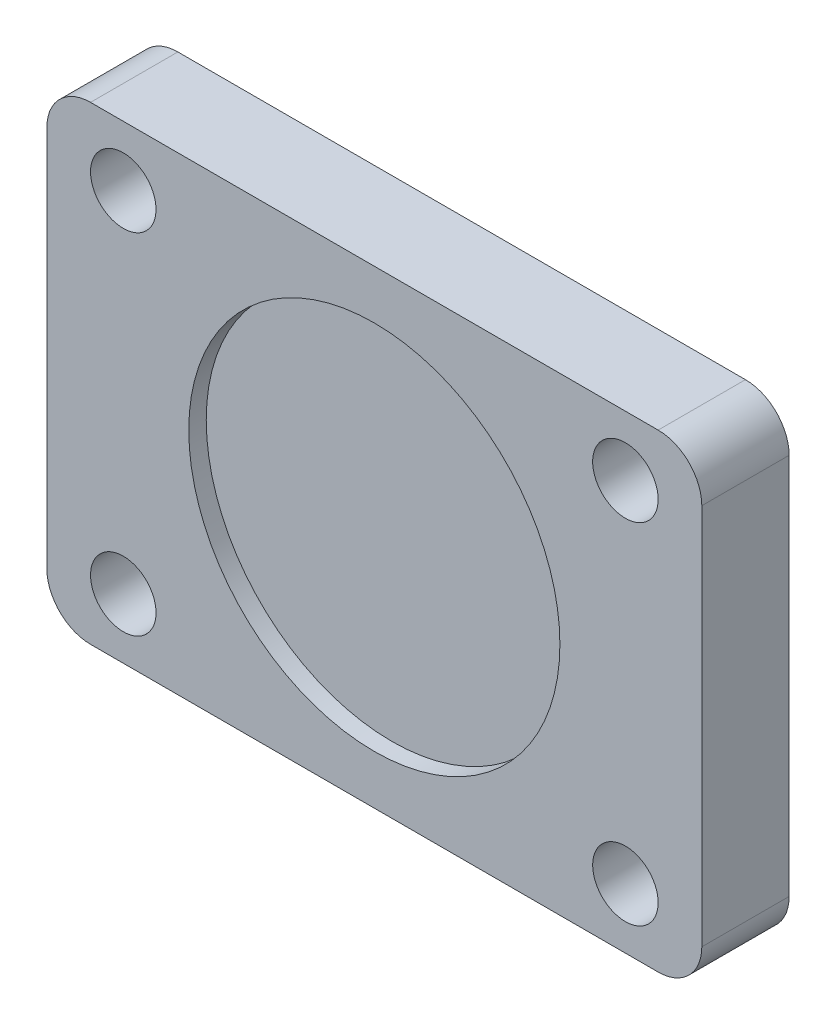
SolidWorks part; units mm, degrees
ref_plane "Front Plane" through (0, 0, 0) normal (0, 0, 1) x (1, 0, 0)
ref_plane "Top Plane" through (0, 0, 0) normal (0, 1, 0) x (1, 0, 0)
ref_plane "Right Plane" through (0, 0, 0) normal (1, 0, 0) x (0, 0, -1)
sketch "Sketch1" plane through (0, 0, 0) normal (0, 0, 1) x (1, 0, 0)
  line L1 (-30, 21.5) -> (30, 21.5)
  line L2 (-30, 21.5) -> (-30, -21.5)
  line L3 (-30, -21.5) -> (30, -21.5)
  line L4 (30, 21.5) -> (30, -21.5)
  line L5 (0, -21.5) -> (0, 21.5) construction
  line L6 (-30, 0) -> (30, 0) construction
  circle A0 centre (23, 16) radius 3
  circle A1 centre (23, -16) radius 3
  circle A2 centre (-23, -16) radius 3
  circle A3 centre (-23, 16) radius 3
  point P0 (0, 0)
  dimension "D3" = 23
  dimension "D4" = 16
  dimension "D5" = 6
  dimension "D1" = 60
  dimension "D2" = 43
extrude "Boss-Extrude1" add sketch "Sketch1" along normal blind 8
fillet "Fillet1" radius 4 4 edges at (30, -21.5, 4) (-30, -21.5, 4) (-30, 21.5, 4) (30, 21.5, 4)
sketch "Sketch2" plane through (0, 0, 8) normal (0, 0, 1) x (1, 0, 0)
  circle A0 centre (0, 0) radius 17
  dimension "D1" = 34
extrude "Cut-Extrude1" cut sketch "Sketch2" against normal blind 1.6
